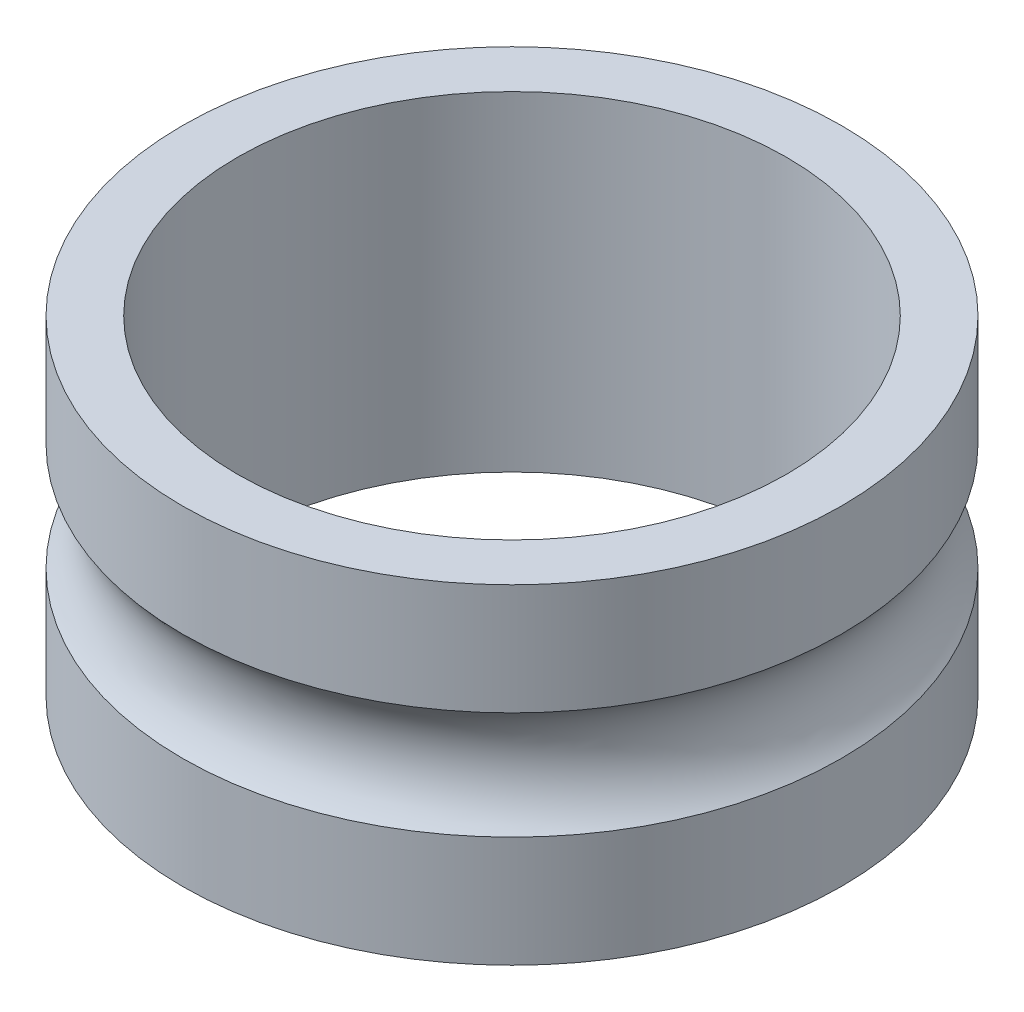
SolidWorks part; units mm, degrees
material "Chrome Stainless Steel"
ref_plane "Front Plane" through (0, 0, 0) normal (0, 0, 1) x (1, 0, 0)
ref_plane "Top Plane" through (0, 0, 0) normal (0, 1, 0) x (1, 0, 0)
ref_plane "Right Plane" through (0, 0, 0) normal (1, 0, 0) x (0, 0, -1)
sketch "Diameter Profile Sketch" plane through (0, 0, 0) normal (0, 1, 0) x (1, 0, 0)
  circle A0 centre (0, 0) radius 2.5
  circle A1 centre (0, 0) radius 3
  dimension "InnerDia" = 5
  dimension "Thickness" = 0.5
extrude "Diameter Profile" add sketch "Diameter Profile Sketch" along normal mid plane 3
sketch "Bearing Path Profile Sketch" plane through (0, 0, 0) normal (0, 0, 1) x (1, 0, 0)
  line L0 (0, 0) -> (3.5, 0) construction
  line L3 (0, 1.5) -> (0, -1.5) construction
  circle A0 centre (3.5, 0) radius 0.7
  dimension "BallDia" = 1.4
  dimension "YDim" = 0.5
  dimension "RefRadius" = 3.5
revolve "Bearing Path Profile" cut sketch "Bearing Path Profile Sketch" angle 360 about axis through (0, 1.5, 0) along (0, -1, 0)
